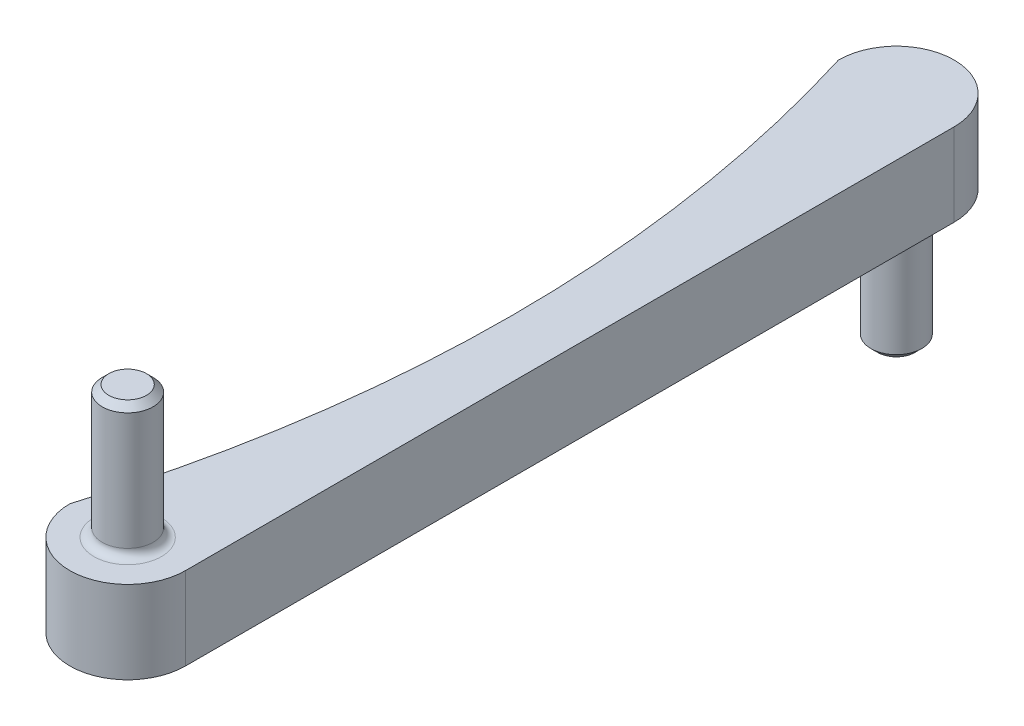
SolidWorks part; units mm, degrees
material "PLA2"
ref_plane "Front Plane" through (0, 0, 0) normal (0, 0, 1) x (1, 0, 0)
ref_plane "Top Plane" through (0, 0, 0) normal (0, 1, 0) x (1, 0, 0)
ref_plane "Right Plane" through (0, 0, 0) normal (1, 0, 0) x (0, 0, -1)
sketch "Sketch1" plane through (0, 0, 0) normal (0, 1, 0) x (1, 0, 0)
  line L0 (0, 0) -> (0, 59.055) construction
  line L3 (-4.445, 0) -> (-4.445, 59.055)
  line L4 (4.445, 0) -> (4.445, 59.055)
  arc A4 (-4.445, 0) -> (4.445, 0) centre (0, 0) ccw
  arc A5 (4.445, 59.055) -> (-4.445, 59.055) centre (0, 59.055) ccw
  point P3 (0, 29.5275)
  dimension "D1" = 8.89
  dimension "D2" = 59.055
extrude "Boss-Extrude1" add sketch "Sketch1" along normal blind 6.35
sketch "Sketch3" plane through (0, 6.35, 0) normal (0, 1, 0) x (1, 0, 0)
  circle A0 centre (0, 0) radius 1.9558
  dimension "D1" = 3.9116
extrude "Boss-Extrude3" add sketch "Sketch3" along normal blind 10.16
sketch "Sketch4" plane through (0, 0, 0) normal (0, -1, 0) x (1, 0, 0)
  circle A0 centre (0, -59.055) radius 1.9558
  dimension "D1" = 3.9116
extrude "Boss-Extrude4" add sketch "Sketch4" along normal blind 10.16
sketch "Sketch5" plane through (0, 6.35, 0) normal (0, 1, 0) x (1, 0, 0)
  line L0 (0, 59.055) -> (0, 0) construction
  line L1 (-4.445, 59.055) -> (-4.445, 0)
  arc A2 (-4.445, 59.055) -> (-4.445, 0) centre (-99.9444, 29.5275) cw
  dimension "D1" = 99.96
extrude "Cut-Extrude1" cut sketch "Sketch5" against normal through all
sketch "Sketch6" plane through (0, 0, 0) normal (0, -1, 0) x (1, 0, 0)
  circle A0 centre (0, -59.055) radius 3.475
  dimension "D1" = 6.95
extrude "Boss-Extrude5" [suppressed] add sketch "Sketch6" along normal blind 2.032
sketch "Sketch7" plane through (0, 6.35, 0) normal (0, 1, 0) x (1, 0, 0)
  circle A0 centre (0, 0) radius 2.77
  dimension "D1" = 5.54
extrude "Boss-Extrude6" [suppressed] add sketch "Sketch7" along normal up to vertex
chamfer "Chamfer1" [suppressed] distance 0.508 angle 45
chamfer "Chamfer3" [suppressed] distance 0.508 angle 45
fillet "Fillet1" [suppressed] radius 0.381
fillet "Fillet2" radius 0.635 2 edges at (0, 0, -57.0992) (0, 6.35, 1.9558)
chamfer "Chamfer4" distance 0.508 angle 45 2 edges at (0, 16.51, 1.9558) (0, -10.16, -61.0108)
